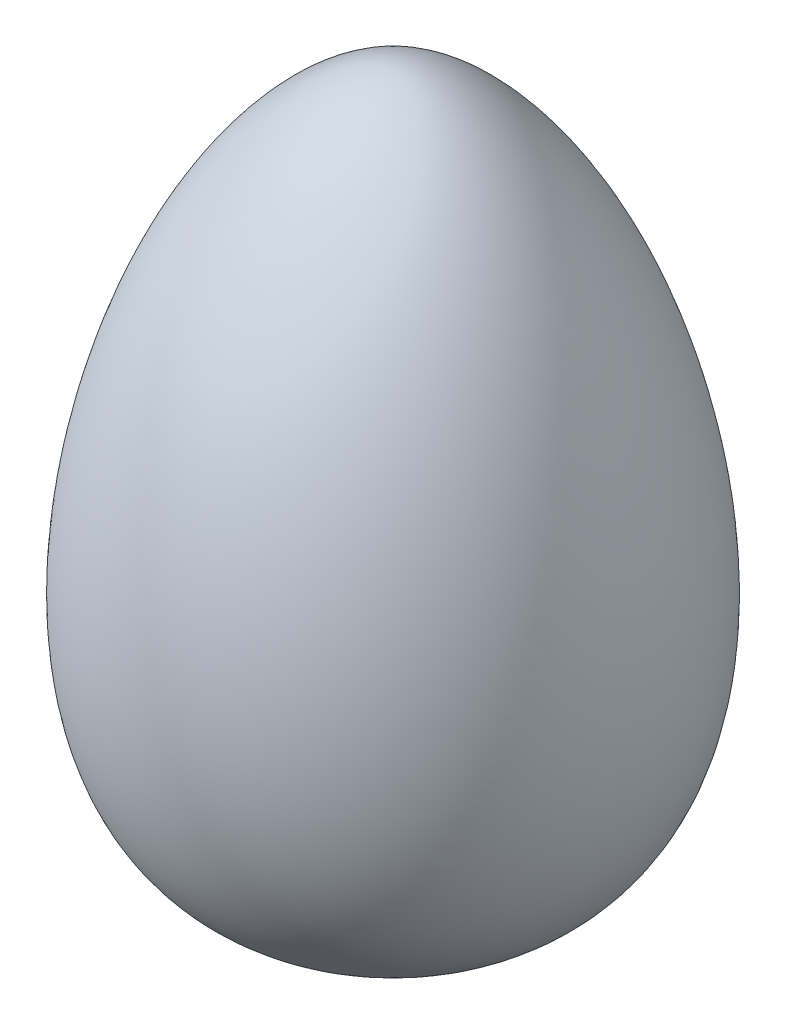
SolidWorks part; units mm, degrees
ref_plane "Front Plane" through (0, 0, 0) normal (0, 0, 1) x (1, 0, 0)
ref_plane "Top Plane" through (0, 0, 0) normal (0, 1, 0) x (1, 0, 0)
ref_plane "Right Plane" through (0, 0, 0) normal (1, 0, 0) x (0, 0, -1)
sketch "Sketch1" plane through (0, 0, 0) normal (0, 0, 1) x (1, 0, 0)
  line L0 (0, 31.5) -> (0, -31.5)
  line L1 (0, 31.5) -> (-21.5, 31.5) construction
  line L2 (-21.5, 31.5) -> (-21.5, -31.5) construction
  line L3 (-21.5, -31.5) -> (0, -31.5) construction
  line L4 (-20.8288, 0) -> (0, 0) construction
  line L5 (-36.5707, -99.3902) -> (-5.2838, 98.1475) construction
  spline S0 degree 3 poles (0, 31.5) (-6.45, 31.5) (-17.3141, 19.7454) (-23.3031, -13.1083) (-18.898, -31.7761) (0, -31.5) knots 0 0 0 0 0.524773 0.624773 1 1 1 1
  dimension "D3" = 63
  dimension "D4" = 21.5
  dimension "D5" = 100
  dimension "D1" = 63
  dimension "D2" = 21.5
  dimension "D6" = 31.5
  dimension "D7" = 99
revolve "Revolve1" add sketch "Sketch1" angle 360 about L0
